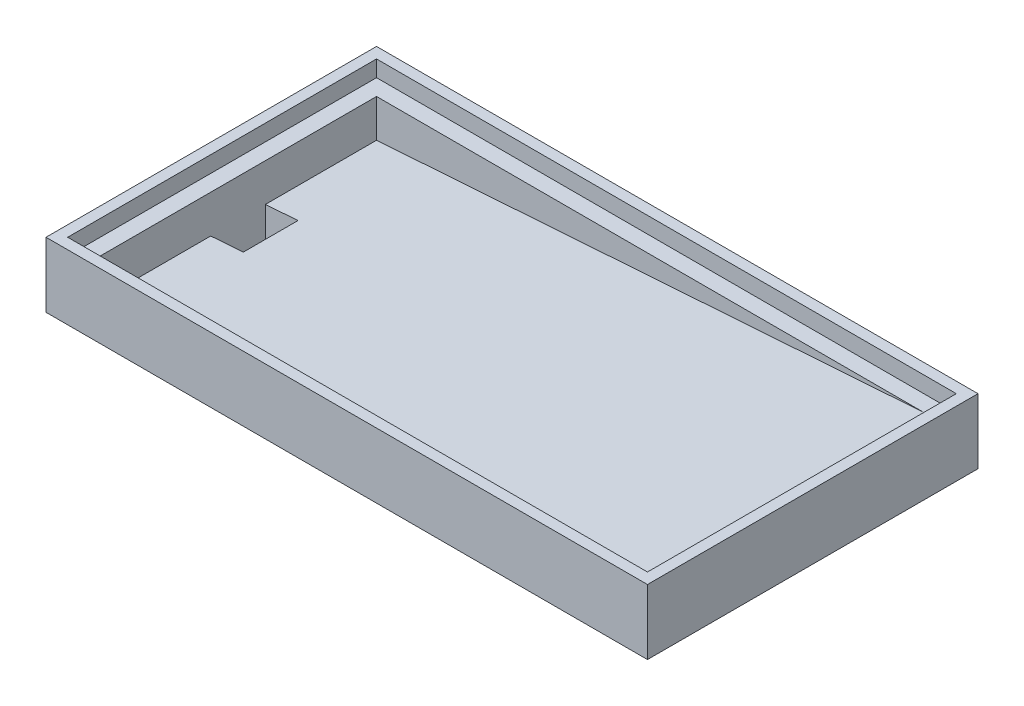
SolidWorks part; units mm, degrees
ref_plane "前基準面" through (0, 0, 0) normal (0, 0, 1) x (1, 0, 0)
ref_plane "上基準面" through (0, 0, 0) normal (0, 1, 0) x (1, 0, 0)
ref_plane "右基準面" through (0, 0, 0) normal (1, 0, 0) x (0, 0, -1)
sketch "草圖1" plane through (0, 0, 0) normal (0, 1, 0) x (1, 0, 0)
  line L1 (0, 0) -> (107, 0)
  line L2 (0, 0) -> (0, 57)
  line L3 (0, 57) -> (107, 57)
  line L4 (107, 0) -> (107, 57)
  dimension "D1" = 57
  dimension "D2" = 107
extrude "伸長-薄件1" add sketch "草圖1" against normal blind 10 thin
sketch "草圖3" plane through (0, -10, 0) normal (0, -1, 0) x (-1, 0, 0)
  line L0 (-109, 59) -> (2, 59) construction
  line L1 (-109, -2) -> (-109, 59) construction
  line L2 (2, -2) -> (-109, -2) construction
  line L3 (2, 59) -> (2, -2) construction
  line L4 (-109, 59) -> (2, 59)
  line L5 (-109, -2) -> (-109, 59)
  line L6 (2, -2) -> (-109, -2)
  line L7 (2, 59) -> (2, -2)
extrude "填料-伸長1" add sketch "草圖3" along normal blind 2
sketch "草圖5" plane through (0, -12, 0) normal (0, -1, 0) x (1, 0, 0)
  line L0 (-2, 2) -> (-2, -59) construction
  line L1 (0, -23.4) -> (27.9998, -23.4)
  line L3 (0, -33.5) -> (27.9998, -33.5)
  line L4 (27.9998, -23.4) -> (27.9998, -33.5)
  line L5 (109, -28.5) -> (0, -28.5) construction
  line L6 (109, -59) -> (109, 2) construction
  line L7 (-2, -33.5) -> (-2, -43.5)
  line L8 (-2, -43.5) -> (37.9998, -43.5)
  line L9 (37.9998, -43.5) -> (37.9998, -13.5)
  line L10 (37.9998, -13.5) -> (-2, -13.5)
  line L11 (-2, -13.5) -> (-2, -23.5)
  line L12 (0, -23.4) -> (0, -33.5)
  dimension "D1" = 5.1
  dimension "D2" = 30
  dimension "D3" = 5
  dimension "D4" = 10
  dimension "D5" = 10
  dimension "D6" = 10
  dimension "D7" = 2
extrude "填料-伸長2" add sketch "草圖5" along normal blind 8
ref_plane "平面1" through (0, -3, 0) normal (0, 1, 0) x (1, 0, 0)
sketch "草圖6" plane through (0, -3, 0) normal (0, 1, 0) x (1, 0, 0)
  line L0 (104, 3) -> (104, 54)
  line L1 (104, 54) -> (3, 54)
  line L2 (3, 54) -> (3, 3)
  line L3 (3, 3) -> (104, 3)
  line L4 (107, 0) -> (107, 57)
  line L5 (107, 57) -> (0, 57)
  line L6 (0, 57) -> (0, 0)
  line L7 (0, 0) -> (107, 0)
  line L8 (107, 0) -> (107, 57)
  line L9 (107, 57) -> (0, 57)
  line L10 (0, 57) -> (0, 0)
  line L11 (0, 0) -> (107, 0)
  dimension "D1" = 0
  dimension "D2" = 3
extrude "填料-伸長3" add sketch "草圖6" against normal up to body separate body
sketch "草圖7" plane through (0, 0, -3) normal (0, 0, -1) x (-1, 0, 0)
  line L0 (-104, -3) -> (-3, -10)
  line L1 (-104, -3) -> (-104, -10)
  line L2 (-104, -10) -> (-3, -10)
extrude "填料-伸長4" add sketch "草圖7" along normal up to next
sketch "草圖8" plane through (0, -12, 0) normal (0, -1, 0) x (1, 0, 0)
  line L5 (0, -33.5) -> (27.9998, -33.5) construction
  line L6 (3, -33.5) -> (9, -33.5)
  line L7 (3, -33.5) -> (3, -23.4)
  line L8 (3, -23.4) -> (9, -23.4)
  line L9 (9, -33.5) -> (9, -23.4)
  line L10 (0, -23.4) -> (27.9998, -23.4) construction
  line L11 (0, -23.4) -> (0, -33.5) construction
  dimension "D1" = 3
  dimension "D2" = 6
extrude "除料-伸長1" cut sketch "草圖8" against normal blind 10
sketch "草圖9" plane through (0, -12, 0) normal (0, -1, 0) x (1, 0, 0)
  line L4 (3, -33.5) -> (3, -23.4)
  line L6 (3, -33.5) -> (3, -23.4)
  line L9 (3, -23.4) -> (0, -23.4)
  line L10 (0, -23.4) -> (0, -33.5)
  line L11 (0, -33.5) -> (3, -33.5)
  line L13 (3, -23.4) -> (0, -23.4)
  line L14 (0, -23.4) -> (0, -33.5)
  line L15 (0, -33.5) -> (3, -33.5)
  dimension "D1" = 0
extrude "填料-伸長7" add sketch "草圖9" along normal up to surface (8 mm away) up to face at (13.9999, -20, -28.45)
